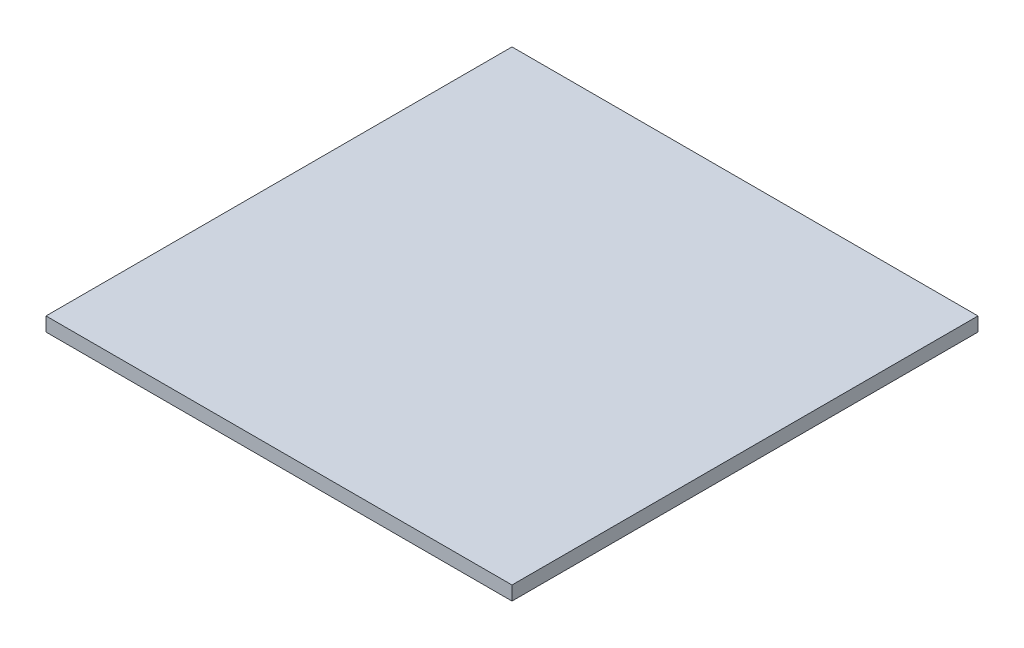
SolidWorks part; units mm, degrees
material "Silicon"
ref_plane "Front Plane" through (0, 0, 0) normal (0, 0, 1) x (1, 0, 0)
ref_plane "Top Plane" through (0, 0, 0) normal (0, 1, 0) x (1, 0, 0)
ref_plane "Right Plane" through (0, 0, 0) normal (1, 0, 0) x (0, 0, -1)
sketch "Sketch1" plane through (0, 0, 0) normal (0, 1, 0) x (1, 0, 0)
  line L1 (0, 0) -> (10, 0)
  line L2 (0, 0) -> (0, -10)
  line L3 (0, -10) -> (10, -10)
  line L4 (10, 0) -> (10, -10)
  dimension "D1" = 10
extrude "Boss-Extrude1" add sketch "Sketch1" along normal blind 0.3
